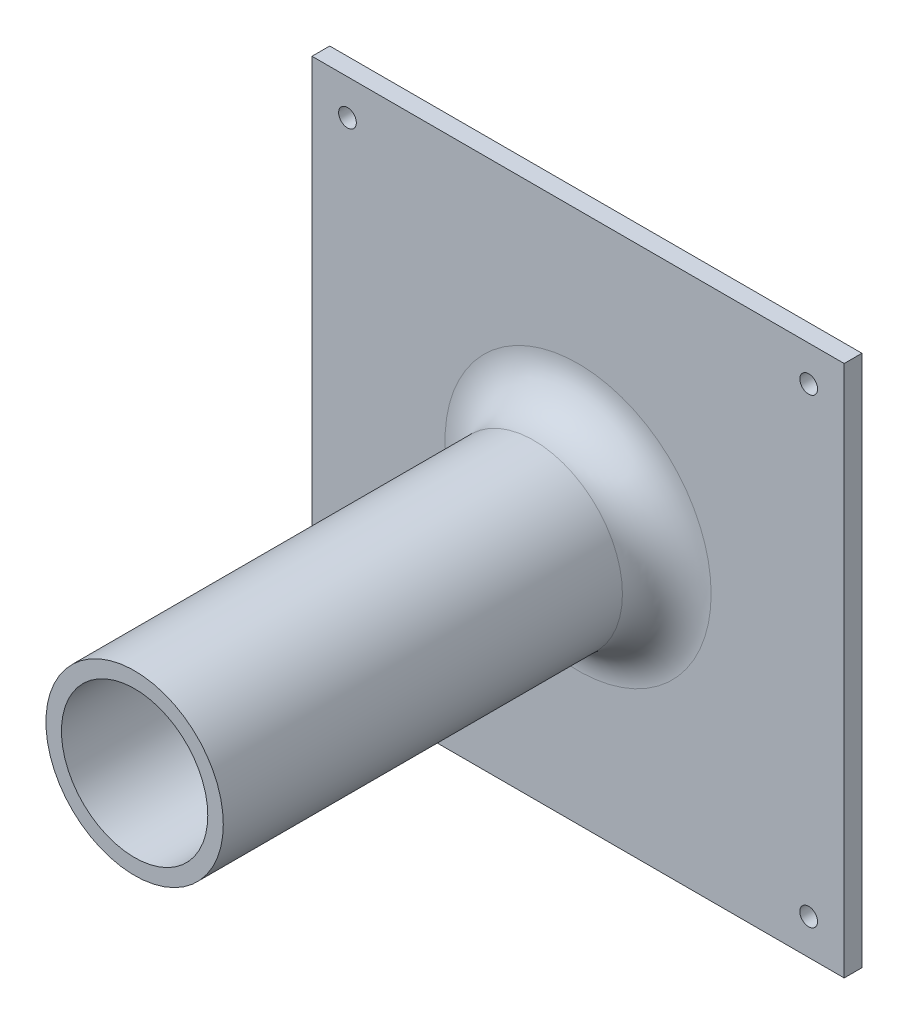
SolidWorks part; units mm, degrees
ref_plane "Plan de face" through (0, 0, 0) normal (0, 0, 1) x (1, 0, 0)
ref_plane "Plan de dessus" through (0, 0, 0) normal (0, 1, 0) x (1, 0, 0)
ref_plane "Plan de droite" through (0, 0, 0) normal (1, 0, 0) x (0, 0, -1)
sketch "Esquisse1" plane through (0, 0, 0) normal (0, 0, 1) x (1, 0, 0)
  line L1 (-30, 30) -> (30, 30)
  line L2 (-30, 30) -> (-30, -30)
  line L3 (-30, -30) -> (30, -30)
  line L4 (30, 30) -> (30, -30)
  circle A0 centre (0, 0) radius 6
  circle A1 centre (-26, 26) radius 1
  circle A2 centre (26, 26) radius 1
  circle A3 centre (26, -26) radius 1
  circle A4 centre (-26, -26) radius 1
  point P4 (0, 30)
  point P5 (-30, 0)
  dimension "D2" = 2
  dimension "D7" = 12
  dimension "D1" = 60
  dimension "D3" = 4
  dimension "D4" = 4
  dimension "D5" = 4
  dimension "D6" = 4
extrude "Boss.-Extru.1" add sketch "Esquisse1" along normal blind 2
sketch "Esquisse2" plane through (0, 0, 2) normal (0, 0, 1) x (1, 0, 0)
  circle A0 centre (0, 0) radius 10
  circle A1 centre (0, 0) radius 8.25
  dimension "D1" = 20
  dimension "D2" = 16.5
extrude "Boss.-Extru.2" add sketch "Esquisse2" along normal blind 50
fillet "Congé1" radius 5 1 edges at (10, 0, 2)
